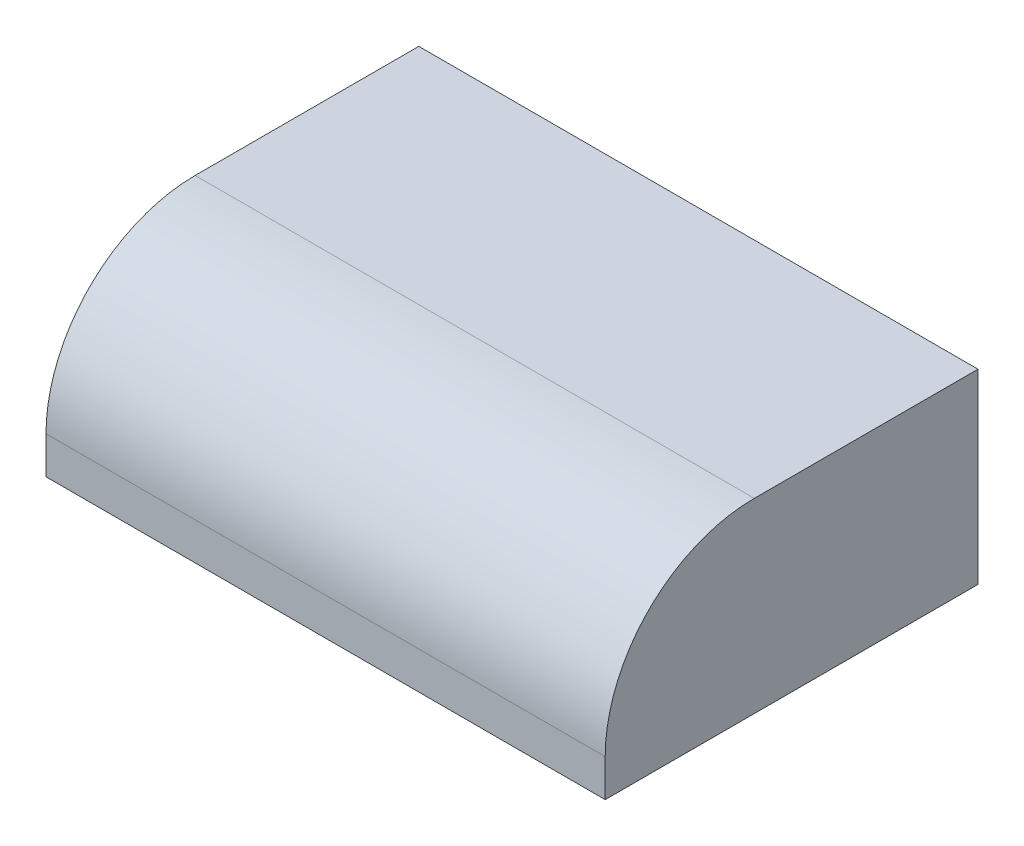
SolidWorks part; units mm, degrees
ref_plane "Front Plane" through (0, 0, 0) normal (0, 0, 1) x (1, 0, 0)
ref_plane "Top Plane" through (0, 0, 0) normal (0, 1, 0) x (1, 0, 0)
ref_plane "Right Plane" through (0, 0, 0) normal (1, 0, 0) x (0, 0, -1)
sketch "Sketch3" plane through (0, 0, 0) normal (0, 1, 0) x (1, 0, 0)
  line L1 (-4.7625, -3.175) -> (4.7625, -3.175)
  line L2 (-4.7625, -3.175) -> (-4.7625, 3.175)
  line L3 (-4.7625, 3.175) -> (4.7625, 3.175)
  line L4 (4.7625, -3.175) -> (4.7625, 3.175)
  line L5 (-4.7625, -3.175) -> (4.7625, 3.175) construction
  line L6 (-4.7625, 3.175) -> (4.7625, -3.175) construction
  point P0 (0, 0)
  dimension "D1" = 6.35
  dimension "D2" = 9.525
extrude "Boss-Extrude3" add sketch "Sketch3" along normal blind 3.175
fillet "Fillet1" radius 2.54 1 edges at (0, 3.175, 3.175)
